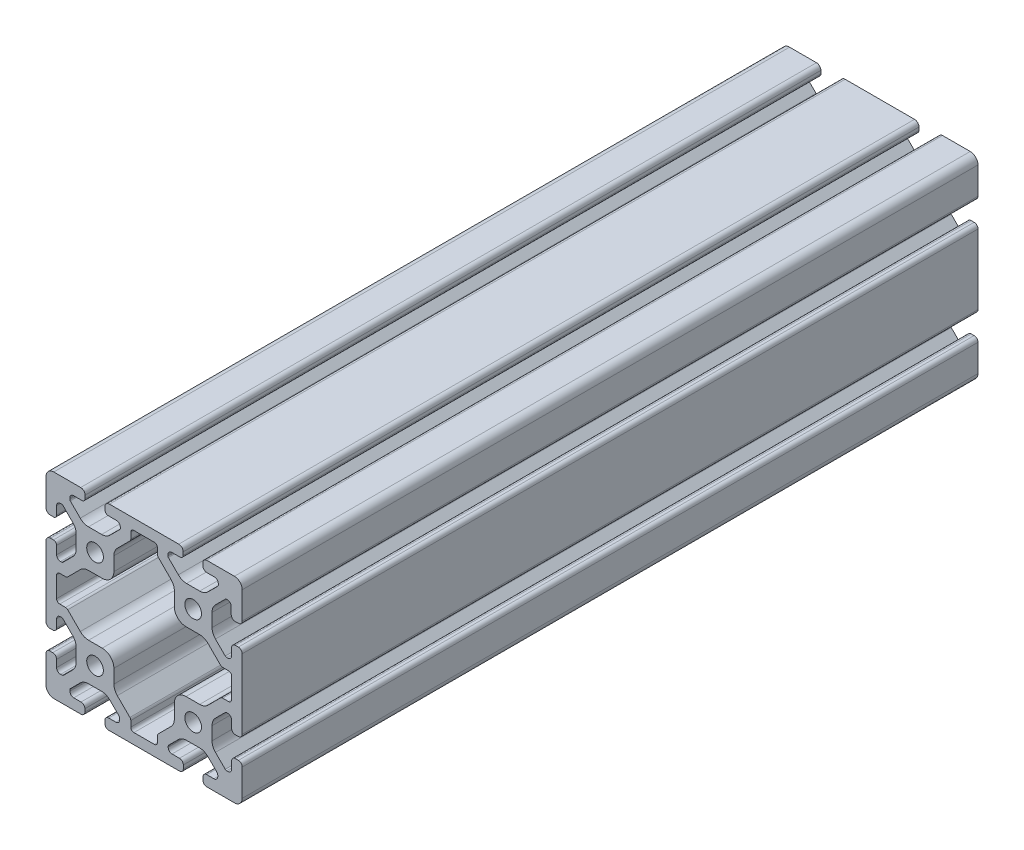
SolidWorks part; units mm, degrees
material "6105-T5 Aluminum"
ref_plane "Front Plane" through (0, 0, 0) normal (0, 0, 1) x (1, 0, 0)
ref_plane "Top Plane" through (0, 0, 0) normal (0, 1, 0) x (1, 0, 0)
ref_plane "Right Plane" through (0, 0, 0) normal (1, 0, 0) x (0, 0, -1)
sketch "Sketch1" plane through (0, 0, 0) normal (0, 0, 1) x (1, 0, 0)
  line L0 (0, -40) -> (0, 40) construction
  line L1 (0, 0) -> (-43.5804, 43.5804) construction
  line L2 (-20, 20) -> (-47.7323, 20) construction
  line L3 (-20, 20) -> (3.796, 43.796) construction
  line L4 (-20, 20) -> (-20, 43.5758) construction
  line L5 (-20, -27.7) -> (-20, -47.5576) construction
  line L131 (29.0912, 26.0365) -> (33.0827, 30.028)
  line L132 (27.7, 17.3222) -> (27.7, 22.6778)
  line L133 (29.0912, 13.9635) -> (33.0827, 9.972)
  line L134 (33.6201, 9.7494) -> (34.11, 9.7494)
  line L135 (35.68, 11.3194) -> (35.68, 14.2221)
  line L136 (37.25, 15.7921) -> (38.43, 15.7921)
  line L137 (40, 14.2221) -> (40, 7.0214)
  line L138 (40, 7.0214) -> (40, -7.0214)
  line L139 (40, -7.0214) -> (40, -14.2221)
  line L140 (38.43, -15.7921) -> (37.25, -15.7921)
  line L141 (35.68, -14.2221) -> (35.68, -11.3194)
  line L142 (33.6201, -9.7494) -> (34.11, -9.7494)
  line L143 (29.0912, -13.9635) -> (33.0827, -9.972)
  line L144 (27.7, -22.6778) -> (27.7, -17.3222)
  line L145 (29.0912, -26.0365) -> (33.0827, -30.028)
  line L146 (33.6201, -30.2506) -> (34.11, -30.2506)
  line L147 (35.68, -28.6806) -> (35.68, -25.7779)
  line L148 (37.25, -24.2079) -> (38.43, -24.2079)
  line L149 (40, -25.7779) -> (40, -33.0259)
  line L150 (40, -33.0259) -> (40, -36.83)
  line L151 (36.83, -40) -> (32.9998, -40)
  line L152 (32.9998, -40) -> (25.5696, -40)
  line L153 (23.9996, -38.43) -> (23.9996, -37.25)
  line L154 (25.5696, -35.68) -> (28.4723, -35.68)
  line L155 (30.0413, -34.0552) -> (30.0171, -33.3605)
  line L156 (29.7949, -32.8496) -> (26.0365, -29.0912)
  line L157 (17.3222, -27.7) -> (22.6778, -27.7)
  line L158 (10.035, -33.0197) -> (13.9635, -29.0912)
  line L159 (9.8124, -33.8926) -> (9.8124, -33.5571)
  line L160 (11.3824, -35.4626) -> (14.4246, -35.4626)
  line L161 (15.9946, -37.0326) -> (15.9946, -38.43)
  line L162 (14.4246, -40) -> (6.9987, -40)
  line L163 (6.9987, -40) -> (-6.9987, -40)
  line L164 (-6.9987, -40) -> (-14.4292, -40)
  line L165 (-15.9992, -38.43) -> (-15.9992, -37.25)
  line L166 (-14.4292, -35.68) -> (-11.5265, -35.68)
  line L167 (-9.9574, -34.0552) -> (-9.9816, -33.3618)
  line L168 (-10.2038, -32.8509) -> (-13.9635, -29.0912)
  line L169 (-22.6778, -27.7) -> (-17.3222, -27.7)
  line L170 (-30.028, -33.0827) -> (-26.0365, -29.0912)
  line L171 (-30.2506, -34.11) -> (-30.2506, -33.6201)
  line L172 (-28.6806, -35.68) -> (-25.7231, -35.68)
  line L173 (-24.1531, -37.25) -> (-24.1531, -38.43)
  line L174 (-25.7231, -40) -> (-33, -40)
  line L175 (-33, -40) -> (-36.83, -40)
  line L176 (-40, -36.83) -> (-40, -33.0191)
  line L177 (-40, -33.0191) -> (-40, -25.591)
  line L178 (-38.43, -24.021) -> (-37.25, -24.021)
  line L179 (-35.68, -28.4937) -> (-35.68, -25.591)
  line L180 (-34.0552, -30.0627) -> (-33.3827, -30.0392)
  line L181 (-32.8718, -29.8171) -> (-29.0912, -26.0365)
  line L182 (-27.7, -22.6778) -> (-27.7, -17.3222)
  line L183 (-29.0912, -13.9635) -> (-33.0827, -9.972)
  line L184 (-34.11, -9.7494) -> (-33.6201, -9.7494)
  line L185 (-35.68, -11.3194) -> (-35.68, -14.4473)
  line L186 (-38.43, -16.0173) -> (-37.25, -16.0173)
  line L187 (-40, -14.4473) -> (-40, -7.0169)
  line L188 (-40, -7.0169) -> (-40, 7.0169)
  line L189 (-40, 7.0169) -> (-40, 14.1348)
  line L190 (-38.1948, 15.94) -> (-36.9772, 15.94)
  line L191 (-35.68, 11.3194) -> (-35.68, 14.6428)
  line L192 (-34.11, 9.7494) -> (-33.6201, 9.7494)
  line L193 (-33.0827, 9.972) -> (-29.0912, 13.9635)
  line L194 (-27.7, 17.3222) -> (-27.7, 22.6778)
  line L195 (-29.0912, 26.0365) -> (-33.0827, 30.028)
  line L196 (-34.11, 30.2506) -> (-33.6201, 30.2506)
  line L197 (-35.68, 28.6806) -> (-35.68, 25.3572)
  line L198 (-38.1948, 24.06) -> (-36.9772, 24.06)
  line L199 (-40, 25.8652) -> (-40, 33.3181)
  line L200 (-40, 33.3181) -> (-40, 36.83)
  line L201 (-36.83, 40) -> (-33.0314, 40)
  line L202 (-33.0314, 40) -> (-25.8652, 40)
  line L203 (-24.06, 36.9772) -> (-24.06, 38.1948)
  line L204 (-25.3572, 35.68) -> (-28.7018, 35.68)
  line L205 (-30.285, 33.6069) -> (-30.285, 34.0968)
  line L206 (-30.0961, 33.1508) -> (-26.0365, 29.0912)
  line L207 (-22.6778, 27.7) -> (-17.3222, 27.7)
  line L208 (-13.9635, 29.0912) -> (-9.9039, 33.1508)
  line L209 (-9.715, 33.6069) -> (-9.715, 34.0968)
  line L210 (-14.6428, 35.68) -> (-11.2982, 35.68)
  line L211 (-15.94, 36.9772) -> (-15.94, 38.1948)
  line L212 (-14.1348, 40) -> (-6.9844, 40)
  line L213 (-6.9844, 40) -> (6.9844, 40)
  line L214 (6.9844, 40) -> (14.1348, 40)
  line L215 (15.94, 36.9772) -> (15.94, 38.1948)
  line L216 (14.6428, 35.68) -> (11.2982, 35.68)
  line L217 (9.715, 33.6069) -> (9.715, 34.0968)
  line L218 (9.9039, 33.1508) -> (13.9635, 29.0912)
  line L219 (17.3222, 27.7) -> (22.6778, 27.7)
  line L220 (26.0365, 29.0912) -> (30.028, 33.0827)
  line L221 (30.2506, 33.6201) -> (30.2506, 34.11)
  line L222 (25.5409, 35.679) -> (28.6258, 35.679)
  line L223 (23.9709, 37.249) -> (23.9709, 38.43)
  line L224 (25.5409, 40) -> (36.83, 40)
  line L226 (40, 36.83) -> (40, 32.9339)
  line L227 (40, 32.9339) -> (40, 25.7779)
  line L228 (38.43, 24.2079) -> (37.0956, 24.2079)
  line L229 (35.5256, 25.7779) -> (35.5256, 28.6806)
  line L230 (33.6201, 30.2506) -> (33.9556, 30.2506)
  line L231 (17.07, 12.32) -> (22.6578, 12.32)
  line L232 (26.0165, 10.9288) -> (31.1439, 5.8014)
  line L233 (32.0419, 5.4294) -> (34.41, 5.4294)
  line L234 (35.68, -4.1594) -> (35.68, 4.1594)
  line L235 (32.0419, -5.4294) -> (34.41, -5.4294)
  line L236 (26.0165, -10.9288) -> (31.1439, -5.8014)
  line L237 (17.07, -12.32) -> (22.6578, -12.32)
  line L238 (12.32, -22.6578) -> (12.32, -17.07)
  line L239 (5.8014, -31.1439) -> (10.9288, -26.0165)
  line L240 (5.4294, -34.41) -> (5.4294, -32.0419)
  line L241 (-4.1594, -35.68) -> (4.1594, -35.68)
  line L242 (-5.4294, -34.41) -> (-5.4294, -32.0419)
  line L243 (-5.8014, -31.1439) -> (-10.9288, -26.0165)
  line L244 (-12.32, -22.6578) -> (-12.32, -17.07)
  line L245 (-22.6578, -12.32) -> (-17.07, -12.32)
  line L246 (-26.0165, -10.9288) -> (-31.1439, -5.8014)
  line L247 (-34.41, -5.4294) -> (-32.0419, -5.4294)
  line L248 (-35.68, -4.1594) -> (-35.68, 4.1594)
  line L249 (-34.41, 5.4294) -> (-32.0419, 5.4294)
  line L250 (-31.1439, 5.8014) -> (-26.0165, 10.9288)
  line L251 (-22.6578, 12.32) -> (-17.07, 12.32)
  line L252 (-12.32, 17.07) -> (-12.32, 22.6578)
  line L253 (-10.9288, 26.0165) -> (-5.8014, 31.1439)
  line L254 (-5.4294, 32.0419) -> (-5.4294, 34.41)
  line L255 (-4.1594, 35.68) -> (4.1594, 35.68)
  line L256 (5.4294, 32.0419) -> (5.4294, 34.41)
  line L257 (5.8014, 31.1439) -> (10.9288, 26.0165)
  line L258 (12.32, 17.07) -> (12.32, 22.6578)
  line L260 (-40, 0) -> (40, 0) construction
  circle A116 centre (-20, 20) radius 3.4
  circle A117 centre (20, 20) radius 3.4
  circle A118 centre (20, -20) radius 3.4
  circle A119 centre (-20, -20) radius 3.4
  arc A120 (29.0912, 26.0365) -> (27.7, 22.6778) centre (32.45, 22.6778) ccw
  arc A121 (27.7, 17.3222) -> (29.0912, 13.9635) centre (32.45, 17.3222) ccw
  arc A122 (33.0827, 9.972) -> (33.6201, 9.7494) centre (33.6201, 10.5094) ccw
  arc A123 (34.11, 9.7494) -> (35.68, 11.3194) centre (34.11, 11.3194) ccw
  arc A124 (37.25, 15.7921) -> (35.68, 14.2221) centre (37.25, 14.2221) ccw
  arc A125 (40, 14.2221) -> (38.43, 15.7921) centre (38.43, 14.2221) ccw
  arc A126 (38.43, -15.7921) -> (40, -14.2221) centre (38.43, -14.2221) ccw
  arc A127 (35.68, -14.2221) -> (37.25, -15.7921) centre (37.25, -14.2221) ccw
  arc A128 (35.68, -11.3194) -> (34.11, -9.7494) centre (34.11, -11.3194) ccw
  arc A129 (33.6201, -9.7494) -> (33.0827, -9.972) centre (33.6201, -10.5094) ccw
  arc A130 (29.0912, -13.9635) -> (27.7, -17.3222) centre (32.45, -17.3222) ccw
  arc A131 (27.7, -22.6778) -> (29.0912, -26.0365) centre (32.45, -22.6778) ccw
  arc A132 (33.0827, -30.028) -> (33.6201, -30.2506) centre (33.6201, -29.4906) ccw
  arc A133 (34.11, -30.2506) -> (35.68, -28.6806) centre (34.11, -28.6806) ccw
  arc A134 (37.25, -24.2079) -> (35.68, -25.7779) centre (37.25, -25.7779) ccw
  arc A135 (40, -25.7779) -> (38.43, -24.2079) centre (38.43, -25.7779) ccw
  arc A136 (36.83, -40) -> (40, -36.83) centre (36.83, -36.83) ccw
  arc A137 (23.9996, -38.43) -> (25.5696, -40) centre (25.5696, -38.43) ccw
  arc A138 (25.5696, -35.68) -> (23.9996, -37.25) centre (25.5696, -37.25) ccw
  arc A139 (28.4723, -35.68) -> (30.0413, -34.0552) centre (28.4723, -34.11) ccw
  arc A140 (30.0171, -33.3605) -> (29.7949, -32.8496) centre (29.2575, -33.387) ccw
  arc A141 (26.0365, -29.0912) -> (22.6778, -27.7) centre (22.6778, -32.45) ccw
  arc A142 (17.3222, -27.7) -> (13.9635, -29.0912) centre (17.3222, -32.45) ccw
  arc A143 (10.035, -33.0197) -> (9.8124, -33.5571) centre (10.5724, -33.5571) ccw
  arc A144 (9.8124, -33.8926) -> (11.3824, -35.4626) centre (11.3824, -33.8926) ccw
  arc A145 (15.9946, -37.0326) -> (14.4246, -35.4626) centre (14.4246, -37.0326) ccw
  arc A146 (14.4246, -40) -> (15.9946, -38.43) centre (14.4246, -38.43) ccw
  arc A147 (-15.9992, -38.43) -> (-14.4292, -40) centre (-14.4292, -38.43) ccw
  arc A148 (-14.4292, -35.68) -> (-15.9992, -37.25) centre (-14.4292, -37.25) ccw
  arc A149 (-11.5265, -35.68) -> (-9.9574, -34.0552) centre (-11.5265, -34.11) ccw
  arc A150 (-9.9816, -33.3618) -> (-10.2038, -32.8509) centre (-10.7412, -33.3883) ccw
  arc A151 (-13.9635, -29.0912) -> (-17.3222, -27.7) centre (-17.3222, -32.45) ccw
  arc A152 (-22.6778, -27.7) -> (-26.0365, -29.0912) centre (-22.6778, -32.45) ccw
  arc A153 (-30.028, -33.0827) -> (-30.2506, -33.6201) centre (-29.4906, -33.6201) ccw
  arc A154 (-30.2506, -34.11) -> (-28.6806, -35.68) centre (-28.6806, -34.11) ccw
  arc A155 (-24.1531, -37.25) -> (-25.7231, -35.68) centre (-25.7231, -37.25) ccw
  arc A156 (-25.7231, -40) -> (-24.1531, -38.43) centre (-25.7231, -38.43) ccw
  arc A157 (-40, -36.83) -> (-36.83, -40) centre (-36.83, -36.83) ccw
  arc A158 (-38.43, -24.021) -> (-40, -25.591) centre (-38.43, -25.591) ccw
  arc A159 (-35.68, -25.591) -> (-37.25, -24.021) centre (-37.25, -25.591) ccw
  arc A160 (-35.68, -28.4937) -> (-34.0552, -30.0627) centre (-34.11, -28.4937) ccw
  arc A161 (-33.3827, -30.0392) -> (-32.8718, -29.8171) centre (-33.4092, -29.2797) ccw
  arc A162 (-29.0912, -26.0365) -> (-27.7, -22.6778) centre (-32.45, -22.6778) ccw
  arc A163 (-27.7, -17.3222) -> (-29.0912, -13.9635) centre (-32.45, -17.3222) ccw
  arc A164 (-33.0827, -9.972) -> (-33.6201, -9.7494) centre (-33.6201, -10.5094) ccw
  arc A165 (-34.11, -9.7494) -> (-35.68, -11.3194) centre (-34.11, -11.3194) ccw
  arc A166 (-37.25, -16.0173) -> (-35.68, -14.4473) centre (-37.25, -14.4473) ccw
  arc A167 (-40, -14.4473) -> (-38.43, -16.0173) centre (-38.43, -14.4473) ccw
  arc A168 (-38.1948, 15.94) -> (-40, 14.1348) centre (-38.1948, 14.1348) ccw
  arc A169 (-35.68, 14.6428) -> (-36.9772, 15.94) centre (-36.9772, 14.6428) ccw
  arc A170 (-35.68, 11.3194) -> (-34.11, 9.7494) centre (-34.11, 11.3194) ccw
  arc A171 (-33.6201, 9.7494) -> (-33.0827, 9.972) centre (-33.6201, 10.5094) ccw
  arc A172 (-29.0912, 13.9635) -> (-27.7, 17.3222) centre (-32.45, 17.3222) ccw
  arc A173 (-27.7, 22.6778) -> (-29.0912, 26.0365) centre (-32.45, 22.6778) ccw
  arc A174 (-33.0827, 30.028) -> (-33.6201, 30.2506) centre (-33.6201, 29.4906) ccw
  arc A175 (-34.11, 30.2506) -> (-35.68, 28.6806) centre (-34.11, 28.6806) ccw
  arc A176 (-36.9772, 24.06) -> (-35.68, 25.3572) centre (-36.9772, 25.3572) ccw
  arc A177 (-40, 25.8652) -> (-38.1948, 24.06) centre (-38.1948, 25.8652) ccw
  arc A178 (-36.83, 40) -> (-40, 36.83) centre (-36.83, 36.83) ccw
  arc A179 (-24.06, 38.1948) -> (-25.8652, 40) centre (-25.8652, 38.1948) ccw
  arc A180 (-25.3572, 35.68) -> (-24.06, 36.9772) centre (-25.3572, 36.9772) ccw
  arc A181 (-28.7018, 35.68) -> (-30.285, 34.0968) centre (-28.7018, 34.0968) ccw
  arc A182 (-30.285, 33.6069) -> (-30.0961, 33.1508) centre (-29.6399, 33.6069) ccw
  arc A183 (-26.0365, 29.0912) -> (-22.6778, 27.7) centre (-22.6778, 32.45) ccw
  arc A184 (-17.3222, 27.7) -> (-13.9635, 29.0912) centre (-17.3222, 32.45) ccw
  arc A185 (-9.9039, 33.1508) -> (-9.715, 33.6069) centre (-10.3601, 33.6069) ccw
  arc A186 (-9.715, 34.0968) -> (-11.2982, 35.68) centre (-11.2982, 34.0968) ccw
  arc A187 (-15.94, 36.9772) -> (-14.6428, 35.68) centre (-14.6428, 36.9772) ccw
  arc A188 (-14.1348, 40) -> (-15.94, 38.1948) centre (-14.1348, 38.1948) ccw
  arc A189 (15.94, 38.1948) -> (14.1348, 40) centre (14.1348, 38.1948) ccw
  arc A190 (14.6428, 35.68) -> (15.94, 36.9772) centre (14.6428, 36.9772) ccw
  arc A191 (11.2982, 35.68) -> (9.715, 34.0968) centre (11.2982, 34.0968) ccw
  arc A192 (9.715, 33.6069) -> (9.9039, 33.1508) centre (10.3601, 33.6069) ccw
  arc A193 (13.9635, 29.0912) -> (17.3222, 27.7) centre (17.3222, 32.45) ccw
  arc A194 (22.6778, 27.7) -> (26.0365, 29.0912) centre (22.6778, 32.45) ccw
  arc A195 (30.028, 33.0827) -> (30.2506, 33.6201) centre (29.4906, 33.6201) ccw
  arc A196 (30.2506, 34.11) -> (28.6258, 35.679) centre (28.6806, 34.11) ccw
  arc A197 (23.9709, 37.249) -> (25.5409, 35.679) centre (25.5409, 37.249) ccw
  arc A198 (25.5409, 40) -> (23.9709, 38.43) centre (25.5409, 38.43) ccw
  arc A199 (40, 36.83) -> (36.83, 40) centre (36.83, 36.83) ccw
  arc A200 (38.43, 24.2079) -> (40, 25.7779) centre (38.43, 25.7779) ccw
  arc A201 (35.5256, 25.7779) -> (37.0956, 24.2079) centre (37.0956, 25.7779) ccw
  arc A202 (35.5256, 28.6806) -> (33.9556, 30.2506) centre (33.9556, 28.6806) ccw
  arc A203 (33.6201, 30.2506) -> (33.0827, 30.028) centre (33.6201, 29.4906) ccw
  arc A204 (26.0165, 10.9288) -> (22.6578, 12.32) centre (22.6578, 7.57) ccw
  arc A205 (31.1439, 5.8014) -> (32.0419, 5.4294) centre (32.0419, 6.6994) ccw
  arc A206 (35.68, 4.1594) -> (34.41, 5.4294) centre (34.41, 4.1594) ccw
  arc A207 (34.41, -5.4294) -> (35.68, -4.1594) centre (34.41, -4.1594) ccw
  arc A208 (32.0419, -5.4294) -> (31.1439, -5.8014) centre (32.0419, -6.6994) ccw
  arc A209 (22.6578, -12.32) -> (26.0165, -10.9288) centre (22.6578, -7.57) ccw
  arc A210 (17.07, -12.32) -> (12.32, -17.07) centre (17.07, -17.07) ccw
  arc A211 (10.9288, -26.0165) -> (12.32, -22.6578) centre (7.57, -22.6578) ccw
  arc A212 (5.8014, -31.1439) -> (5.4294, -32.0419) centre (6.6994, -32.0419) ccw
  arc A213 (4.1594, -35.68) -> (5.4294, -34.41) centre (4.1594, -34.41) ccw
  arc A214 (-5.4294, -34.41) -> (-4.1594, -35.68) centre (-4.1594, -34.41) ccw
  arc A215 (-5.4294, -32.0419) -> (-5.8014, -31.1439) centre (-6.6994, -32.0419) ccw
  arc A216 (-12.32, -22.6578) -> (-10.9288, -26.0165) centre (-7.57, -22.6578) ccw
  arc A217 (-12.32, -17.07) -> (-17.07, -12.32) centre (-17.07, -17.07) ccw
  arc A218 (-26.0165, -10.9288) -> (-22.6578, -12.32) centre (-22.6578, -7.57) ccw
  arc A219 (-31.1439, -5.8014) -> (-32.0419, -5.4294) centre (-32.0419, -6.6994) ccw
  arc A220 (-35.68, -4.1594) -> (-34.41, -5.4294) centre (-34.41, -4.1594) ccw
  arc A221 (-34.41, 5.4294) -> (-35.68, 4.1594) centre (-34.41, 4.1594) ccw
  arc A222 (-32.0419, 5.4294) -> (-31.1439, 5.8014) centre (-32.0419, 6.6994) ccw
  arc A223 (-22.6578, 12.32) -> (-26.0165, 10.9288) centre (-22.6578, 7.57) ccw
  arc A224 (-17.07, 12.32) -> (-12.32, 17.07) centre (-17.07, 17.07) ccw
  arc A225 (-10.9288, 26.0165) -> (-12.32, 22.6578) centre (-7.57, 22.6578) ccw
  arc A226 (-5.8014, 31.1439) -> (-5.4294, 32.0419) centre (-6.6994, 32.0419) ccw
  arc A227 (-4.1594, 35.68) -> (-5.4294, 34.41) centre (-4.1594, 34.41) ccw
  arc A228 (5.4294, 34.41) -> (4.1594, 35.68) centre (4.1594, 34.41) ccw
  arc A229 (5.4294, 32.0419) -> (5.8014, 31.1439) centre (6.6994, 32.0419) ccw
  arc A230 (12.32, 22.6578) -> (10.9288, 26.0165) centre (7.57, 22.6578) ccw
  arc A231 (12.32, 17.07) -> (17.07, 12.32) centre (17.07, 17.07) ccw
  dimension "D8" = 6.8
  dimension "D1" = 80
  dimension "D2" = 40
  dimension "D3" = 20
  dimension "D4" = 20.57
  dimension "D5" = 4.32
  dimension "D6" = 4.32
  dimension "D7" = 8.12
  dimension "D9" = 4.32
  dimension "D10" = 12.3
extrude "Extrude1" add sketch "Sketch1" against normal blind 300
